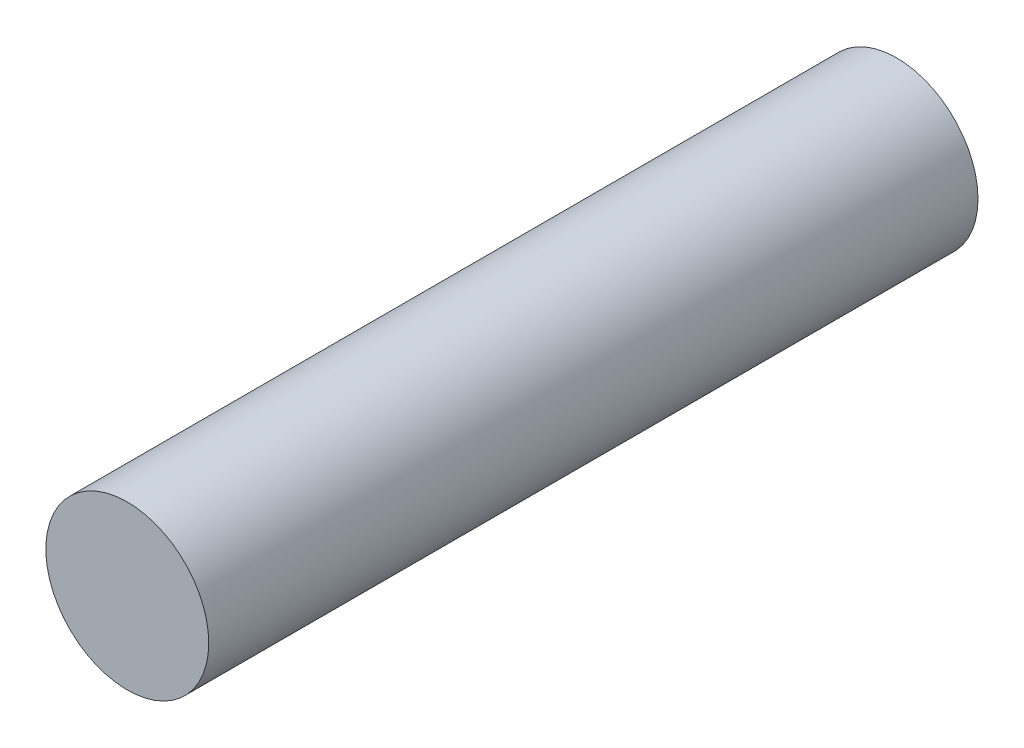
SolidWorks part; units mm, degrees
ref_plane "前视基准面" through (0, 0, 0) normal (0, 0, 1) x (1, 0, 0)
ref_plane "上视基准面" through (0, 0, 0) normal (0, 1, 0) x (1, 0, 0)
ref_plane "右视基准面" through (0, 0, 0) normal (1, 0, 0) x (0, 0, -1)
sketch "草图1" plane through (0, 0, 0) normal (0, 0, 1) x (1, 0, 0)
  circle A0 centre (0, 0) radius 9
  dimension "D1" = 18
extrude "凸台-拉伸1" add sketch "草图1" along normal blind 85
